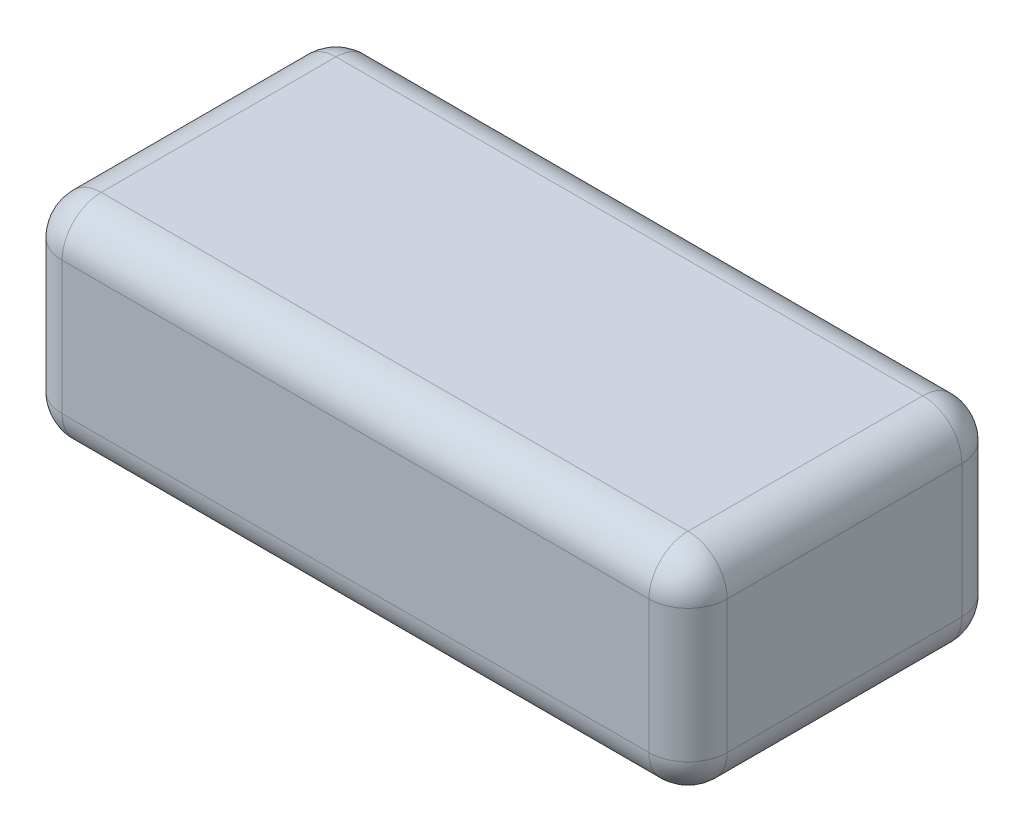
SolidWorks part; units mm, degrees
ref_plane "前视基准面" through (0, 0, 0) normal (0, 0, 1) x (1, 0, 0)
ref_plane "上视基准面" through (0, 0, 0) normal (0, 1, 0) x (1, 0, 0)
ref_plane "右视基准面" through (0, 0, 0) normal (1, 0, 0) x (0, 0, -1)
sketch "草图1" plane through (0, 0, 0) normal (0, 1, 0) x (1, 0, 0)
  line L1 (42.5, -20) -> (-42.5, -20)
  line L2 (42.5, -20) -> (42.5, 20)
  line L3 (42.5, 20) -> (-42.5, 20)
  line L4 (-42.5, -20) -> (-42.5, 20)
  line L5 (42.5, -20) -> (-42.5, 20) construction
  line L6 (42.5, 20) -> (-42.5, -20) construction
  point P0 (0, 0)
extrude "凸台-拉伸1" add sketch "草图1" along normal mid plane 27
fillet "圆角1" radius 5 12 edges at (-42.5, 0, -20) (0, -13.5, -20) (42.5, 0, -20) (42.5, -13.5, 0) (-42.5, 0, 20) (42.5, 0, 20) (0, -13.5, 20) (0, 13.5, -20) (42.5, 13.5, 0) (0, 13.5, 20) (-42.5, 13.5, 0) (-42.5, -13.5, 0)
